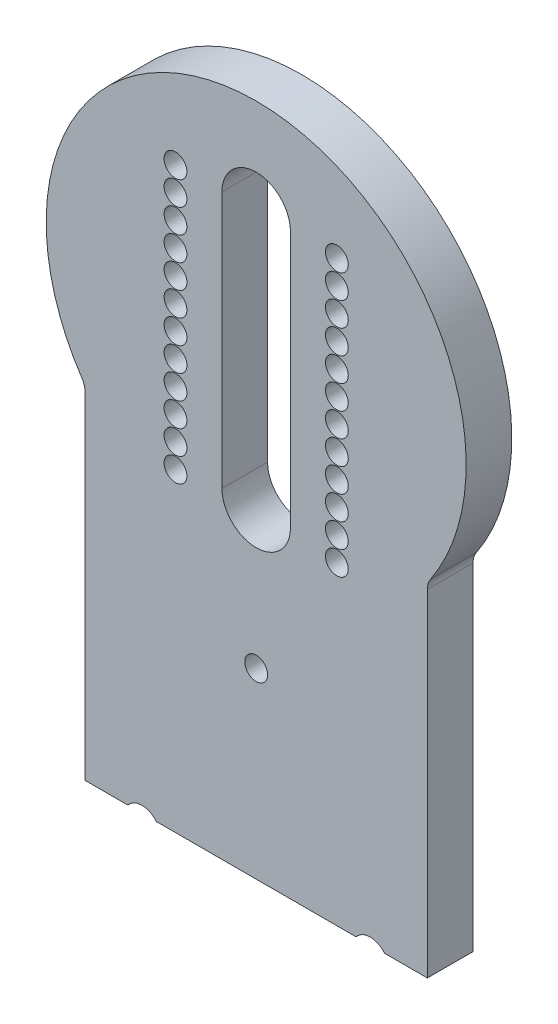
SolidWorks part; units mm, degrees
material "Aleación 1060"
ref_plane "Alzado" through (0, 0, 0) normal (0, 0, 1) x (1, 0, 0)
ref_plane "Planta" through (0, 0, 0) normal (0, 1, 0) x (1, 0, 0)
ref_plane "Vista lateral" through (0, 0, 0) normal (1, 0, 0) x (0, 0, -1)
sketch "Croquis1" plane through (0, 0, 0) normal (0, 0, 1) x (1, 0, 0)
  line L0 (-3, 0) -> (3, 0) construction
  line L1 (3, 0) -> (3, 10)
  line L2 (3, 0) -> (3, -12.5)
  line L3 (0, 0) -> (7.07, 0) construction
  line L4 (5.72, 0) -> (5.72, 10) construction
  line L5 (5.72, 0) -> (5.72, -12.5) construction
  line L6 (8.42, 10) -> (8.42, -12.5) construction
  line L7 (0, 0) -> (0, 18.4) construction
  line L8 (-8.42, 10) -> (-8.42, -12.5) construction
  line L9 (-5.72, 0) -> (-5.72, -12.5) construction
  line L10 (-5.72, 0) -> (-5.72, 10) construction
  line L11 (-3, 0) -> (-3, -12.5)
  line L12 (-3, 0) -> (-3, 10)
  line L13 (0, -18.4) -> (-15, -18.4) construction
  line L14 (-15, -10.6565) -> (-15, -40.6565)
  line L15 (15, -10.6565) -> (15, -40.6565)
  line L16 (-15, -40.6565) -> (15, -40.6565)
  arc A0 (15, -10.6565) -> (-15, -10.6565) centre (0, 0) ccw
  arc A1 (5.72, 10) -> (8.42, 10) centre (7.07, 10) cw construction
  arc A2 (5.72, -12.5) -> (8.42, -12.5) centre (7.07, -12.5) ccw construction
  arc A3 (-5.72, -12.5) -> (-8.42, -12.5) centre (-7.07, -12.5) cw construction
  arc A4 (-5.72, 10) -> (-8.42, 10) centre (-7.07, 10) ccw construction
  arc A5 (-3, 10) -> (3, 10) centre (0, 10) cw
  arc A6 (-3, -12.5) -> (3, -12.5) centre (0, -12.5) ccw
  circle A7 centre (-7.07, 10) radius 1
  circle A8 centre (7.07, 10) radius 1
  circle A9 centre (-7.07, 7.9) radius 1
  circle A10 centre (7.07, 7.9) radius 1
  circle A11 centre (-7.07, 5.8) radius 1
  circle A12 centre (7.07, 5.8) radius 1
  circle A13 centre (-7.07, 3.7) radius 1
  circle A14 centre (7.07, 3.7) radius 1
  circle A15 centre (-7.07, 1.6) radius 1
  circle A16 centre (7.07, 1.6) radius 1
  circle A17 centre (-7.07, -0.5) radius 1
  circle A18 centre (7.07, -0.5) radius 1
  circle A19 centre (-7.07, -2.6) radius 1
  circle A20 centre (7.07, -2.6) radius 1
  circle A21 centre (-7.07, -4.7) radius 1
  circle A22 centre (7.07, -4.7) radius 1
  circle A23 centre (-7.07, -6.8) radius 1
  circle A24 centre (7.07, -6.8) radius 1
  circle A25 centre (-7.07, -8.9) radius 1
  circle A26 centre (7.07, -8.9) radius 1
  circle A27 centre (-7.07, -11) radius 1
  circle A28 centre (7.07, -11) radius 1
  circle A29 centre (-7.07, -13.1) radius 1
  circle A30 centre (7.07, -13.1) radius 1
  dimension "D1" = 36.8
  dimension "D10" = 2
  dimension "D11" = 2
  dimension "D2" = 10
  dimension "D3" = 12.5
  dimension "D4" = 2.7
  dimension "D5" = 15
  dimension "D6" = 30
  dimension "D7" = 3
  dimension "D8" = 7.07
  dimension "D9" = 12.5
  dimension "D12" = 12
extrude "Saliente-Extruir1" add sketch "Croquis1" along normal blind 4
sketch "Croquis3" plane through (0, -40.6565, 0) normal (0, -1, 0) x (1, 0, 0)
  line L0 (-15, 4) -> (-15, 0) construction
  line L1 (0, 0) -> (0, 4) construction
  line L2 (-15, 0) -> (15, 0) construction
  line L3 (-15, 4) -> (15, 4) construction
  circle A0 centre (-10, 2) radius 1.25
  circle A1 centre (10, 2) radius 1.25
  dimension "D1" = 2.5
  dimension "D2" = 5
extrude "Cortar-Extruir1" cut sketch "Croquis3" against normal blind 4
sketch "Croquis4" plane through (0, 0, 4) normal (0, 0, 1) x (1, 0, 0)
  line L0 (-15, -40.6565) -> (15, -40.6565) construction
  line L1 (15, -40.6565) -> (15, -10.6565) construction
  line L2 (0, -40.6565) -> (0, -41.1697) construction
  circle A0 centre (10, -41.6565) radius 1.6
  circle A1 centre (-10, -41.6565) radius 1.6
  dimension "D1" = 3.2
  dimension "D2" = 1
  dimension "D3" = 5
extrude "Cortar-Extruir2" cut sketch "Croquis4" against normal up to vertex (4 mm away)
fillet "Redondeo1" radius 1.6 2 edges at (15, -10.6565, 2) (-15, -10.6565, 2)
sketch "Croquis5" plane through (0, 0, 4) normal (0, 0, 1) x (1, 0, 0)
  line L0 (-8.751, -40.6565) -> (8.751, -40.6565) construction
  circle A0 centre (0, -24.6565) radius 1
  point P5 (0, -40.6565)
  dimension "D1" = 2
  dimension "D2" = 16
extrude "Cortar-Extruir3" cut sketch "Croquis5" against normal up to vertex (4 mm away)
